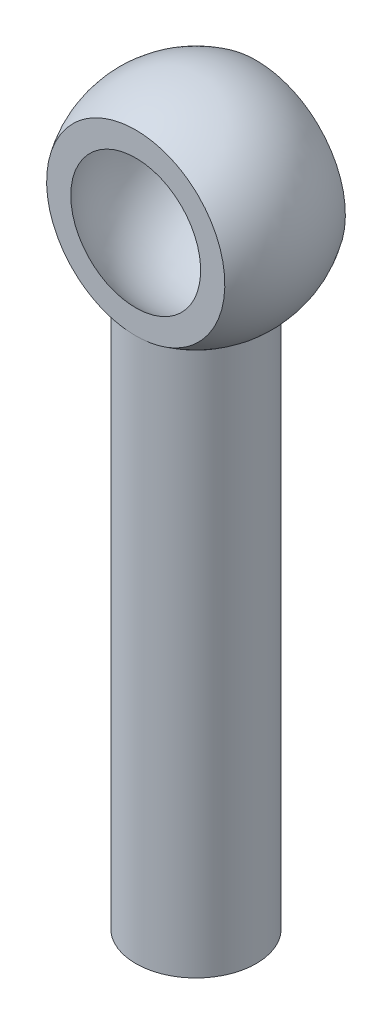
SolidWorks part; units mm, degrees
ref_plane "Front Plane" through (0, 0, 0) normal (0, 0, 1) x (1, 0, 0)
ref_plane "Top Plane" through (0, 0, 0) normal (0, 1, 0) x (1, 0, 0)
ref_plane "Right Plane" through (0, 0, 0) normal (1, 0, 0) x (0, 0, -1)
sketch "Sketch1" plane through (0, 0, 0) normal (0, 1, 0) x (1, 0, 0)
  circle A0 centre (0, 0) radius 4.7625
extrude "Boss-Extrude1" add sketch "Sketch1" along normal blind 50
sketch "Sketch2" plane through (0, 0, 0) normal (0, 0, 1) x (1, 0, 0)
  line L1 (0, 58.5) -> (0, 41.5)
  line L2 (0, -5.2387) -> (0, 5.2387) construction
  line L3 (4.7625, 50) -> (-4.7625, 50) construction
  arc A1 (0, 58.5) -> (0, 41.5) centre (0, 50) ccw
  dimension "D1" = 17
  dimension "D2" = 0
revolve "Revolve4" add sketch "Sketch2" angle 360 about L1
sketch "Sketch4" plane through (0, 0, 0) normal (1, 0, 0) x (0, 0, -1)
  line L1 (-4.7625, 42.9595) -> (-9.7625, 42.9595)
  line L2 (-4.7625, 42.9595) -> (-4.7625, 57.5)
  line L3 (-4.7625, 57.5) -> (-9.7625, 57.5)
  line L4 (-9.7625, 42.9595) -> (-9.7625, 57.5)
  line L9 (4.76, 42.9595) -> (9.76, 42.9595)
  line L10 (4.76, 42.9595) -> (4.76, 57.5)
  line L11 (9.76, 42.9595) -> (9.76, 57.5)
  line L12 (4.76, 57.5) -> (9.76, 57.5)
  line L13 (0, 9.35) -> (0, -9.35) construction
  arc A0 (4.7625, 42.9595) -> (-4.7625, 42.9595) centre (0, 50) ccw construction
  dimension "D1" = 7.5
  dimension "D2" = 5
  dimension "D3" = 5
  dimension "D4" = 4.7625
  dimension "D5" = 4.76
extrude "Cut-Extrude2" cut sketch "Sketch4" against normal through all and the other way through all
sketch "Sketch5" plane through (0, 0, 0) normal (0, 0, 1) x (1, 0, 0)
  line L0 (0, 58.5) -> (0, 41.5) construction
  line L1 (0, 57) -> (0, 43)
  arc A0 (0, 57) -> (0, 43) centre (0, 50) ccw
  dimension "D1" = 14
revolve "Cut-Revolve1" cut sketch "Sketch5" angle 360 about L1
